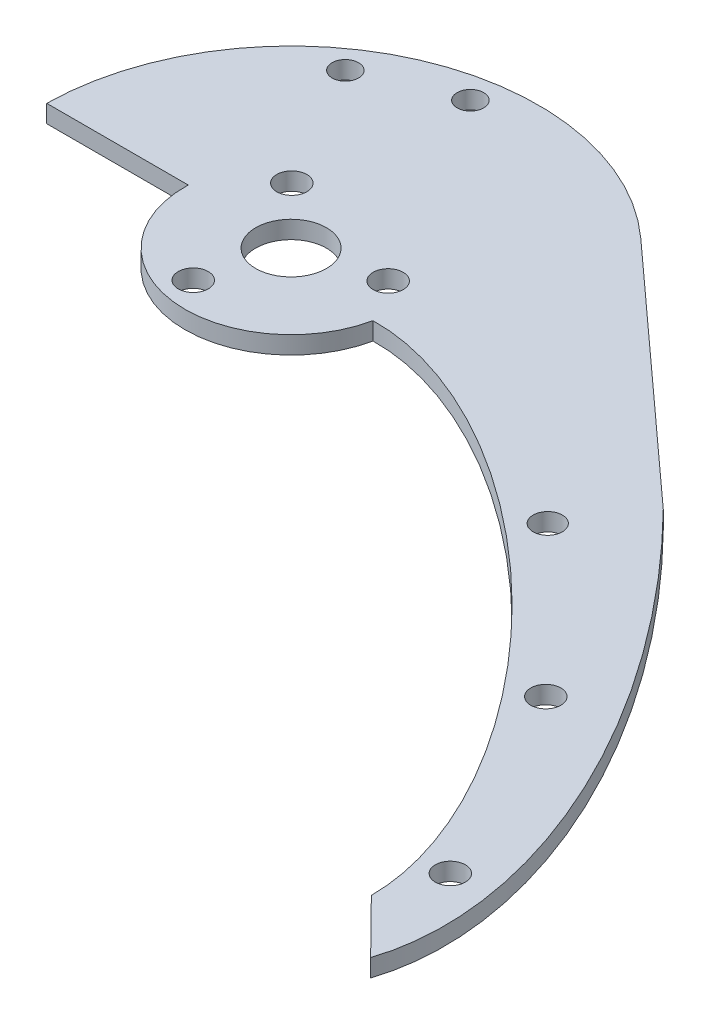
SolidWorks part; units mm, degrees
ref_plane "Спереди" through (0, 0, 0) normal (0, 0, 1) x (1, 0, 0)
ref_plane "Сверху" through (0, 0, 0) normal (0, 1, 0) x (1, 0, 0)
ref_plane "Справа" through (0, 0, 0) normal (1, 0, 0) x (0, 0, -1)
sketch "Эскиз1" plane through (0, 0, 0) normal (0, 1, 0) x (1, 0, 0)
  line L0 (-11.9945, 0.3627) -> (-27.9977, 0.3627)
  line L1 (65.3336, -66.1855) -> (70.2512, -71.1672) construction
  line L2 (-19.6703, 19.9268) -> (70.2512, -71.1672) construction
  line L3 (0, 0) -> (-9.6836, 9.8099) construction
  line L4 (46.6406, -4.5449) -> (18.8288, 20.7238)
  line L5 (0, 0) -> (13.3374, 3.4813) construction
  line L6 (0, 0) -> (-4.7339, -17.2201) construction
  line L8 (67.9375, -58.8591) -> (73.9918, -64.9924)
  line L11 (0, 0) -> (70.2512, -71.1672) construction
  arc A0 (0, 28) -> (-27.9977, 0.3627) centre (0, 0) ccw
  arc A1 (0, 28) -> (18.8288, 20.7238) centre (0, 0) cw
  circle A2 centre (0, 0) radius 9 construction
  circle A3 centre (0, 0) radius 10.7 construction
  circle A4 centre (-6.3226, 6.4051) radius 1.7
  circle A5 centre (0, 0) radius 4
  circle A6 centre (8.7082, 2.273) radius 1.7
  circle A7 centre (-2.3856, -8.6781) radius 1.7
  arc A8 (-11.9945, 0.3627) -> (11.7418, -2.4759) centre (0, 0) ccw
  ellipse E0 centre (25.2904, -25.6202) end of major axis (70.2512, -71.1672) minor radius 30 (70.2512, -71.1672) -> (46.6406, -4.5449) ccw construction
  ellipse E1 centre (35.1256, -35.5836) end of major axis (4.9176, -4.9817) minor radius 18 (65.3336, -66.1855) -> (11.7418, -2.4759) ccw construction
  ellipse E3 centre (25.2904, -25.6202) end of major axis (70.2512, -71.1672) minor radius 30 (46.6406, -4.5449) -> (73.9918, -64.9924) cw
  ellipse E4 centre (35.1256, -35.5836) end of major axis (4.9176, -4.9817) minor radius 18 (67.9375, -58.8591) -> (11.7418, -2.4759) ccw
  dimension "D1" = 28
  dimension "D2" = 18
  dimension "D6" = 18
  dimension "D7" = 12
  dimension "D9" = 120
  dimension "D4" = 8
  dimension "D8" = 21.4
  dimension "D3" = 50
  dimension "D5" = 7
  dimension "D10" = 120
  dimension "D11" = 30
  dimension "D12" = 7
extrude "Бобышка-Вытянуть1" add sketch "Эскиз1" along normal blind 2
sketch "Эскиз2" plane through (0, 2, 0) normal (0, 1, 0) x (1, 0, 0)
  line L0 (0, 0) -> (0, 16.5609) construction
  line L1 (0, 0) -> (-2.989, 16.9517) construction
  line L2 (0, 0) -> (-6.9675, 16.8209) construction
  line L3 (0, 0) -> (70.2512, -71.1672) construction
  line L4 (35.1256, -35.5836) -> (46.9107, 7.2861) construction
  line L5 (35.1256, -35.5836) -> (100.3884, -66.5324) construction
  line L6 (35.1256, -35.5836) -> (113.1257, -15.2242) construction
  circle A0 centre (0, 0) radius 25 construction
  circle A1 centre (-4.3412, 24.6202) radius 1.5
  circle A2 centre (-14.3394, 20.4788) radius 1.5
  circle A3 centre (58.3341, -29.5258) radius 1.7
  circle A4 centre (70.2579, -52.244) radius 1.7
  circle A5 centre (41.4836, -12.4555) radius 1.65
  ellipse E0 centre (35.1256, -35.5836) end of major axis (67.7924, -68.6764) minor radius 21.5 construction
  dimension "D2" = 22.5
  dimension "D3" = 50
  dimension "D4" = 3
  dimension "D7" = 21.5
  dimension "D9" = 120
  dimension "D10" = 3.4
  dimension "D11" = 3.4
  dimension "D1" = 10
  dimension "D5" = 20
  dimension "D6" = 60
  dimension "D8" = 46.5
extrude "Вырез-Вытянуть2" cut sketch "Эскиз2" against normal through all
